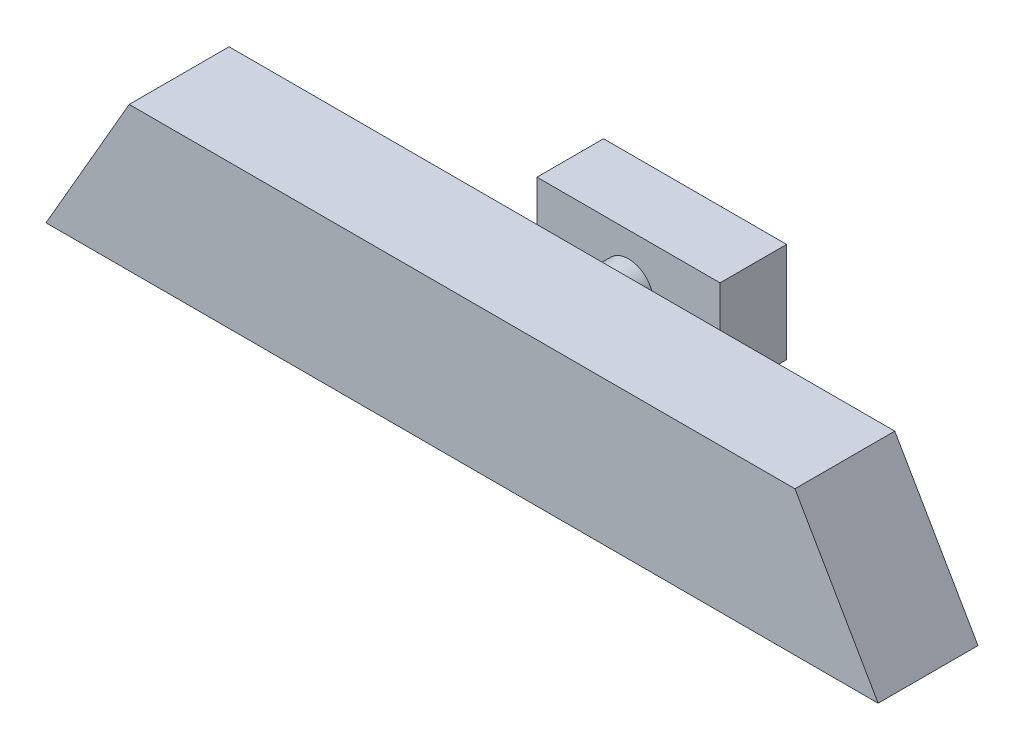
SolidWorks part; units mm, degrees
material "橡胶"
ref_plane "前视基准面" through (0, 0, 0) normal (0, 0, 1) x (1, 0, 0)
ref_plane "上视基准面" through (0, 0, 0) normal (0, 1, 0) x (1, 0, 0)
ref_plane "右视基准面" through (0, 0, 0) normal (1, 0, 0) x (0, 0, -1)
sketch "草图1" plane through (0, 0, 0) normal (0, 0, 1) x (1, 0, 0)
  line L0 (-52.4608, 0) -> (197.5392, 0)
  line L1 (197.5392, 0) -> (172.5392, 43.3013)
  line L2 (172.5392, 43.3013) -> (-27.4608, 43.3013)
  line L3 (-27.4608, 43.3013) -> (-52.4608, 0)
  dimension "D1" = 200
  dimension "D2" = 250
  dimension "D3" = 50
  dimension "D4" = 50
extrude "凸台-拉伸1" add sketch "草图1" along normal blind 30
sketch "草图2" plane through (0, 0, 0) normal (0, 0, -1) x (-1, 0, 0)
  circle A0 centre (-72.5392, 20.6267) radius 7.5
  dimension "D2" = 15
  dimension "D1" = 100
extrude "凸台-拉伸2" add sketch "草图2" along normal blind 20
sketch "草图3" plane through (0, 0, -20) normal (0, 0, -1) x (-1, 0, 0)
  line L1 (-45.0392, 5.6267) -> (-100.0392, 5.6267)
  line L2 (-45.0392, 5.6267) -> (-45.0392, 35.6267)
  line L3 (-45.0392, 35.6267) -> (-100.0392, 35.6267)
  line L4 (-100.0392, 5.6267) -> (-100.0392, 35.6267)
  line L5 (-45.0392, 5.6267) -> (-100.0392, 35.6267) construction
  line L6 (-45.0392, 35.6267) -> (-100.0392, 5.6267) construction
  point P0 (-72.5392, 20.6267)
  dimension "D1" = 55
  dimension "D2" = 30
extrude "凸台-拉伸3" add sketch "草图3" along normal blind 20
sketch "草图4" plane through (0, 0, -40) normal (0, 0, -1) x (-1, 0, 0)
  circle A0 centre (-72.5392, 20.6267) radius 5
extrude "切除-拉伸1" cut sketch "草图4" against normal blind 10
